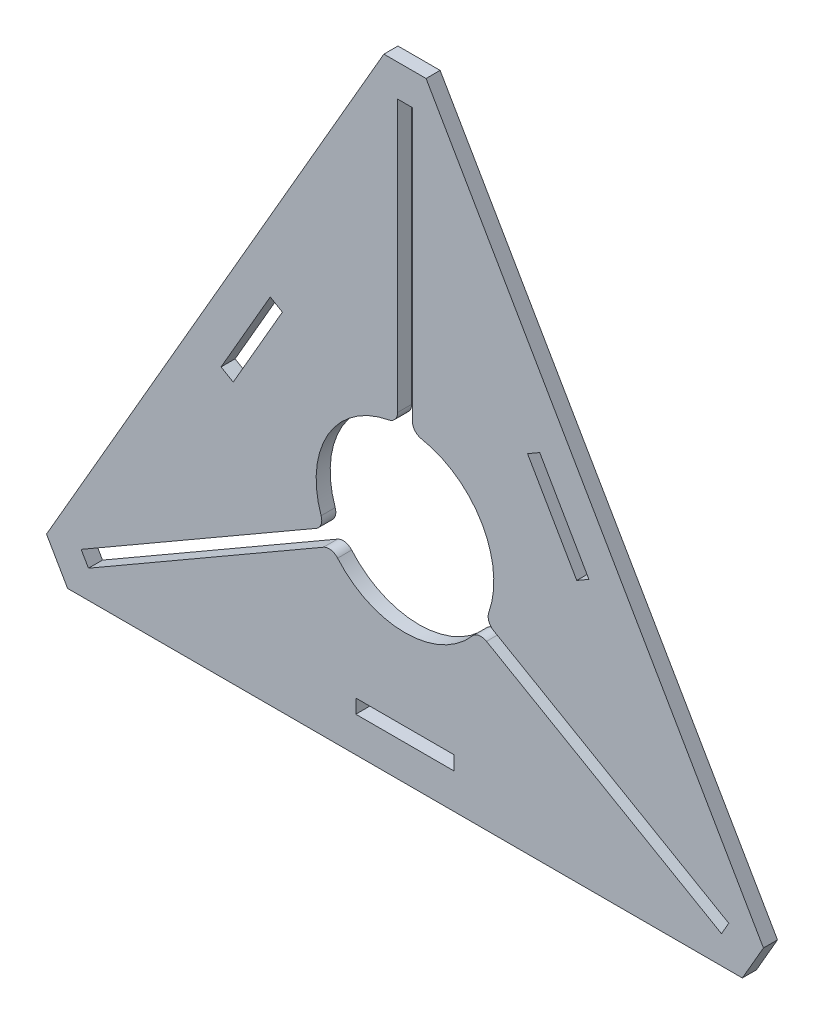
SolidWorks part; units mm, degrees
ref_plane "Front Plane" through (0, 0, 0) normal (0, 0, 1) x (1, 0, 0)
ref_plane "Top Plane" through (0, 0, 0) normal (0, 1, 0) x (1, 0, 0)
ref_plane "Right Plane" through (0, 0, 0) normal (1, 0, 0) x (0, 0, -1)
sketch "Sketch1" plane through (0, 0, 0) normal (0, 0, 1) x (1, 0, 0)
  line L0 (0, 0) -> (0, 146.6407) construction
  line L1 (-3.302, 166.9959) -> (3.302, 166.9959)
  line L2 (-3.302, 166.9959) -> (-3.302, 44.4282)
  line L4 (3.302, 166.9959) -> (3.302, 44.4282)
  line L5 (-3.302, 166.9959) -> (3.302, 39.9959) construction
  line L6 (-3.302, 39.9959) -> (3.302, 166.9959) construction
  line L7 (146.2737, -80.6383) -> (142.9717, -86.3576)
  line L8 (142.9717, -86.3576) -> (36.825, -25.0737)
  line L9 (146.2737, -80.6383) -> (40.127, -19.3545)
  line L10 (146.2737, -80.6383) -> (32.9865, -22.8576) construction
  line L11 (0, 0) -> (126.9945, -73.3203) construction
  line L12 (36.2885, -17.1383) -> (142.9717, -86.3576) construction
  line L13 (-142.9717, -86.3576) -> (-146.2737, -80.6383)
  line L14 (-146.2737, -80.6383) -> (-40.127, -19.3545)
  line L15 (-142.9717, -86.3576) -> (-36.825, -25.0737)
  line L16 (-142.9717, -86.3576) -> (-36.2885, -17.1383) construction
  line L17 (0, 0) -> (-126.9945, -73.3203) construction
  line L18 (-32.9865, -22.8576) -> (-146.2737, -80.6383) construction
  line L19 (0, -98.9867) -> (152.4, -98.9867)
  line L21 (0, -98.9867) -> (-152.4, -98.9867)
  line L22 (0, 0) -> (0, -98.9867) construction
  line L23 (-161.925, -82.4889) -> (-9.525, 181.4756)
  line L24 (-9.525, 181.4756) -> (9.525, 181.4756)
  line L25 (-161.925, -82.4889) -> (-152.4, -98.9867)
  line L26 (152.4, -98.9867) -> (161.925, -82.4889)
  line L27 (161.925, -82.4889) -> (9.525, 181.4756)
  line L28 (0, 0) -> (150.3753, 86.8192) construction
  line L29 (-22.225, -76.7617) -> (22.225, -76.7617)
  line L30 (-22.225, -76.7617) -> (-22.225, -83.1117)
  line L31 (-22.225, -83.1117) -> (22.225, -83.1117)
  line L32 (22.225, -76.7617) -> (22.225, -83.1117)
  line L33 (-22.225, -76.7617) -> (22.225, -83.1117) construction
  line L34 (-22.225, -83.1117) -> (22.225, -76.7617) construction
  line L35 (0, 0) -> (-132.9552, 76.7617) construction
  line L36 (-83.0893, 22.3084) -> (-60.8643, 60.8033)
  line L37 (-60.8643, 60.8033) -> (-55.3651, 57.6283)
  line L38 (-55.3651, 57.6283) -> (-77.5901, 19.1334)
  line L39 (-77.5901, 19.1334) -> (-83.0893, 22.3084)
  line L40 (-80.3397, 20.7209) -> (-58.1147, 59.2158) construction
  line L41 (60.8643, 60.8033) -> (55.3651, 57.6283)
  line L42 (83.0893, 22.3084) -> (60.8643, 60.8033)
  line L43 (77.5901, 19.1334) -> (83.0893, 22.3084)
  line L44 (55.3651, 57.6283) -> (77.5901, 19.1334)
  arc A0 (-7.4402, 39.4363) -> (-37.8729, -13.2747) centre (0, 0) ccw
  arc A1 (-30.4327, -26.1615) -> (30.4327, -26.1615) centre (0, 0) ccw
  arc A2 (37.8729, -13.2747) -> (7.4402, 39.4363) centre (0, 0) ccw
  arc A3 (-37.8729, -13.2747) -> (-40.127, -19.3545) centre (-42.667, -14.9551) cw
  arc A4 (-36.825, -25.0737) -> (-30.4327, -26.1615) centre (-34.285, -29.4731) cw
  arc A5 (30.4327, -26.1615) -> (36.825, -25.0737) centre (34.285, -29.4731) cw
  arc A6 (37.8729, -13.2747) -> (40.127, -19.3545) centre (42.667, -14.9551) ccw
  arc A7 (7.4402, 39.4363) -> (3.302, 44.4282) centre (8.382, 44.4282) cw
  arc A8 (-7.4402, 39.4363) -> (-3.302, 44.4282) centre (-8.382, 44.4282) ccw
  point P3 (0, 103.4959)
  point P20 (0, 0)
  point P38 (157.1625, -90.7378)
  point P45 (0, 181.4756)
  point P46 (-157.1625, -90.7378)
  point P47 (0, -79.9367)
  point P52 (-85.725, 49.4934)
  point P55 (85.725, 49.4934)
  point P58 (-66.4776, 38.3809)
  dimension "D1" = 80.264
  dimension "D5" = 5.08
  dimension "D2" = 127
  dimension "D3" = 6.604
  dimension "D6" = 19.05
  dimension "D7" = 304.8
  dimension "D8" = 152.4
  dimension "D9" = 6.35
  dimension "D10" = 19.05
  dimension "D11" = 19.05
  dimension "D12" = 44.45
  dimension "D13" = 19.05
  dimension "D14" = 6.35
  dimension "D15" = 44.45
  dimension "D16" = 19.05
  dimension "D4" = 3
extrude "Boss-Extrude1" add sketch "Sketch1" along normal blind 6.35
